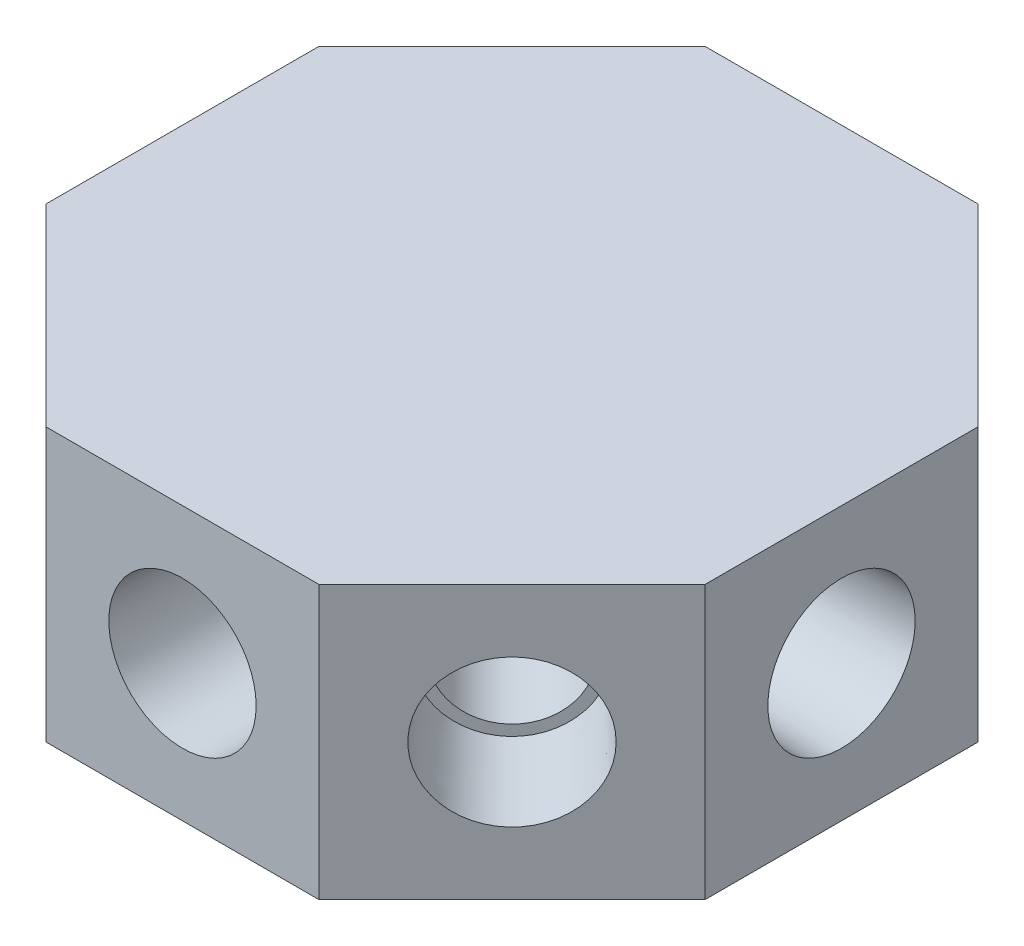
SolidWorks part; units mm, degrees
ref_plane "Front Plane" through (0, 0, 0) normal (0, 0, 1) x (1, 0, 0)
ref_plane "Top Plane" through (0, 0, 0) normal (0, 1, 0) x (1, 0, 0)
ref_plane "Right Plane" through (0, 0, 0) normal (1, 0, 0) x (0, 0, -1)
sketch "Sketch1" plane through (0, 0, 0) normal (0, 1, 0) x (1, 0, 0)
  line L0 (12.7, -30.6605) -> (30.6605, -12.7)
  line L1 (30.6605, 12.7) -> (12.7, 30.6605)
  line L2 (12.7, 30.6605) -> (-12.7, 30.6605)
  line L3 (-12.7, 30.6605) -> (-30.6605, 12.7)
  line L4 (-30.6605, 12.7) -> (-30.6605, -12.7)
  line L5 (-30.6605, -12.7) -> (-12.7, -30.6605)
  line L6 (-12.7, -30.6605) -> (12.7, -30.6605)
  line L7 (30.6605, -12.7) -> (30.6605, 12.7)
  circle A0 centre (0, 0) radius 30.6605 construction
  dimension "D1" = 25.4
extrude "Boss-Extrude1" add sketch "Sketch1" along normal blind 25.4
hole_wizard "1/4 NPT Tapped Hole1" positions "Sketch3" profile "Sketch2" size "1/4" standard "ANSI Inch"
sketch "Sketch3" plane through (0, 0, 0) normal (0, -1, 0) x (-1, 0, 0)
  point P0 (0, 0)
sketch "Sketch2" plane through (0, 0, 0) normal (1, 0, 0) x (0, 0, -1)
  line L0 (0, 0) -> (0, 20.3603)
  line L1 (5.5626, 17.018) -> (0, 20.3603)
  line L2 (-5.5626, 17.018) -> (0, 20.3603) construction
  line L3 (5.5626, 17.018) -> (5.5626, 9.906)
  line L4 (5.5626, 9.906) -> (6.558, 9.906)
  line L5 (6.558, 9.906) -> (6.8546, 0)
  line L6 (-6.558, 9.906) -> (-6.8546, 0) construction
  line L7 (6.8546, 0) -> (0, 0)
  line L8 (0, -6.35) -> (0, 107.95) construction
  line L11 (-5.5626, 9.906) -> (-6.558, 9.906) construction
  dimension "Tap Drill Dia." = 11.1252
  dimension "Tap Drill Depth" = 17.018
  dimension "Thread Dia." = 13.7092
  dimension "Thread Angle" = 3.43
  dimension "Thread Depth" = 9.906
  dimension "Drill Angle" = 118
hole_wizard "1/4 NPT Tapped Hole2" positions "Sketch5" profile "Sketch4" size "1/4" standard "ANSI Inch"
sketch "Sketch5" plane through (-21.6803, 0, 21.6803) normal (-0.7071, 0, 0.7071) x (0.7071, 0, 0.7071)
  line L0 (0, 0) -> (0, 25.4) construction
  line L1 (-12.7, 0) -> (12.7, 0) construction
  line L2 (-12.7, 25.4) -> (12.7, 25.4) construction
  point P0 (0, 12.7)
sketch "Sketch4" plane through (-21.6803, 12.7, 21.6803) normal (0, 1, 0) x (0.7071, 0, 0.7071)
  line L0 (0, 0) -> (0, 20.3603)
  line L1 (5.5626, 17.018) -> (0, 20.3603)
  line L2 (-5.5626, 17.018) -> (0, 20.3603) construction
  line L3 (5.5626, 17.018) -> (5.5626, 9.906)
  line L4 (5.5626, 9.906) -> (6.558, 9.906)
  line L5 (6.558, 9.906) -> (6.8546, 0)
  line L6 (-6.558, 9.906) -> (-6.8546, 0) construction
  line L7 (6.8546, 0) -> (0, 0)
  line L8 (0, -6.35) -> (0, 107.95) construction
  line L11 (-5.5626, 9.906) -> (-6.558, 9.906) construction
  dimension "Tap Drill Dia." = 11.1252
  dimension "Tap Drill Depth" = 17.018
  dimension "Thread Dia." = 13.7092
  dimension "Thread Angle" = 3.43
  dimension "Thread Depth" = 9.906
  dimension "Drill Angle" = 118
sketch "Sketch7" plane through (-21.6803, 0, 21.6803) normal (-0.7071, 0, 0.7071) x (0.7071, 0, 0.7071)
  circle A0 centre (0, 12.7) radius 5.5626
  circle A1 centre (0, 12.7) radius 5.5626 construction
extrude "Cut-Extrude2" cut sketch "Sketch7" against normal up to next
pattern_circular "CirPattern1" count 8 over 360 about axis through (0, 0, 0) along (0, 1, 0) of "1/4 NPT Tapped Hole2", "Cut-Extrude2"
